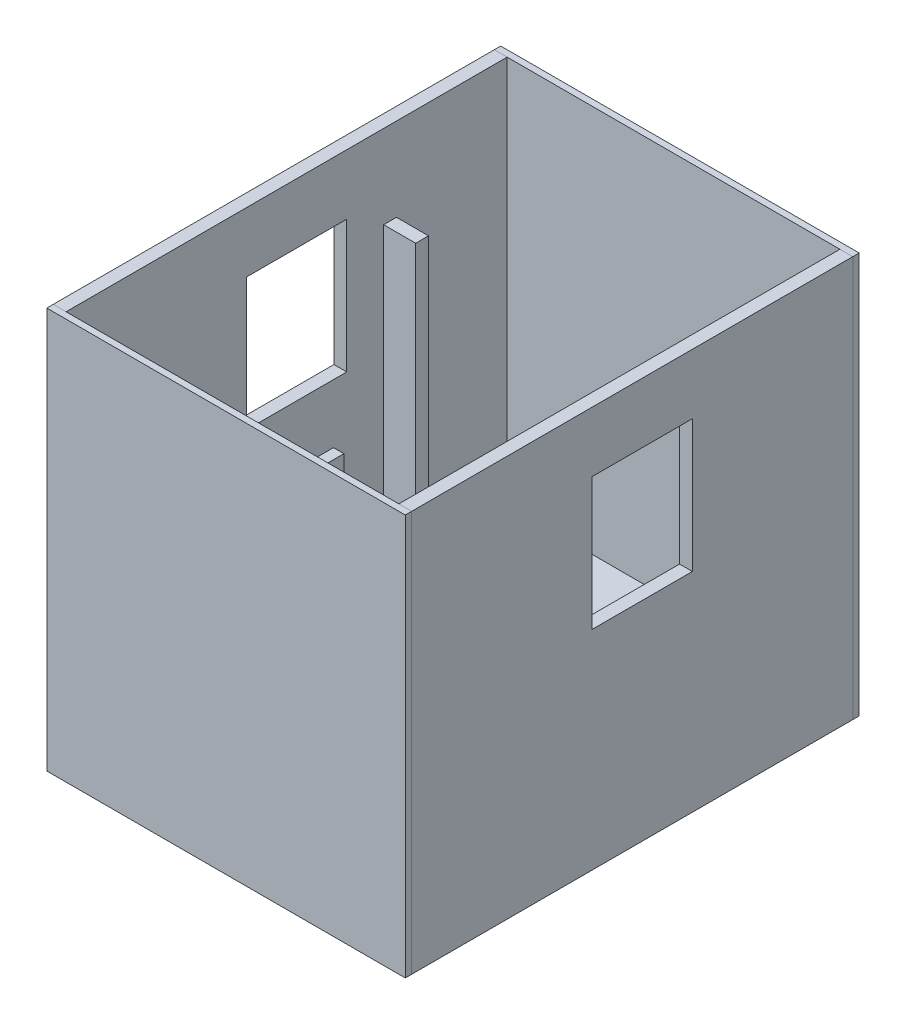
SolidWorks part; units mm, degrees
material "Pin"
ref_plane "Plan de face" through (0, 0, 0) normal (0, 0, 1) x (1, 0, 0)
ref_plane "Plan de dessus" through (0, 0, 0) normal (0, 1, 0) x (1, 0, 0)
ref_plane "Plan de droite" through (0, 0, 0) normal (1, 0, 0) x (0, 0, -1)
sketch "Esquisse1" plane through (0, 0, 0) normal (0, 1, 0) x (1, 0, 0)
  line L1 (0, 0) -> (415, 0)
  line L2 (0, 0) -> (0, 550)
  line L3 (0, 550) -> (415, 550)
  line L4 (415, 0) -> (415, 550)
  dimension "D1" = 550
  dimension "D2" = 415
extrude "Boss.-Extru.1" add sketch "Esquisse1" along normal blind 16
sketch "Esquisse2" plane through (0, 0, -500) normal (1, 0, 0) x (0, 0, -1)
  line L1 (-208, 16) -> (-195, 16)
  line L2 (-208, 16) -> (-208, 43)
  line L3 (-208, 43) -> (-195, 43)
  line L4 (-195, 16) -> (-195, 43)
  line L5 (50, 16) -> (50, 0) construction
  line L6 (-101, 16) -> (-88, 16)
  line L7 (-101, 16) -> (-101, 43)
  line L8 (-101, 43) -> (-88, 43)
  line L9 (-88, 16) -> (-88, 43)
  line L10 (50, 16) -> (-500, 16) construction
  dimension "D1" = 138
  dimension "D2" = 120
  dimension "D3" = 27
  dimension "D4" = 13
extrude "Boss.-Extru.2" add sketch "Esquisse2" along normal blind 335 from offset 40 separate body
sketch "Esquisse3" plane through (0, 0, 0) normal (0, 1, 0) x (1, 0, 0)
  line L0 (0, 0) -> (415, 0) construction
  line L1 (0, 550) -> (-16, 550)
  line L2 (0, 550) -> (0, 0)
  line L3 (0, 0) -> (-16, 0)
  line L4 (-16, 550) -> (-16, 0)
  line L6 (415, 550) -> (431, 550)
  line L7 (415, 550) -> (415, 0)
  line L8 (415, 0) -> (431, 0)
  line L9 (431, 550) -> (431, 0)
  dimension "D1" = 16
extrude "Boss.-Extru.3" add sketch "Esquisse3" along normal blind 500 separate body
sketch "Esquisse4" plane through (-16, 0, 0) normal (-1, 0, 0) x (0, 0, 1)
  line L0 (-550, 500) -> (-550, 0) construction
  line L1 (-350, 425) -> (-225, 425)
  line L2 (-350, 425) -> (-350, 260)
  line L3 (-350, 260) -> (-225, 260)
  line L4 (-225, 425) -> (-225, 260)
  line L5 (-550, 500) -> (0, 500) construction
  line L6 (0, 500) -> (0, 0) construction
  dimension "D1" = 125
  dimension "D2" = 165
  dimension "D3" = 75
  dimension "D4" = 200
  dimension "D5" = 225
extrude "Enlèv. mat.-Extru.1" cut sketch "Esquisse4" against normal through all
sketch "Esquisse5" plane through (0, 16, 0) normal (0, 1, 0) x (1, 0, 0)
  line L0 (0, 550) -> (0, 0) construction
  line L1 (415, 0) -> (415, 550) construction
  line L2 (375, 292) -> (40, 292) construction
  line L8 (0, 141) -> (415, 141)
  line L9 (0, 141) -> (0, 157)
  line L10 (0, 157) -> (415, 157)
  line L11 (415, 141) -> (415, 157)
  dimension "D1" = 16
  dimension "D2" = 135
extrude "Boss.-Extru.4" add sketch "Esquisse5" along normal blind 320 separate body
sketch "Esquisse6" plane through (0, 0, -550) normal (0, 0, -1) x (-1, 0, 0)
  line L1 (-431, 0) -> (16, 0)
  line L2 (-431, 0) -> (-431, 500)
  line L3 (-431, 500) -> (16, 500)
  line L4 (16, 0) -> (16, 500)
extrude "Boss.-Extru.5" add sketch "Esquisse6" along normal blind 8 separate body
sketch "Esquisse7" plane through (0, 0, 0) normal (0, 0, 1) x (1, 0, 0)
  line L1 (-16, 500) -> (431, 500)
  line L2 (-16, 500) -> (-16, 0)
  line L3 (-16, 0) -> (431, 0)
  line L4 (431, 500) -> (431, 0)
extrude "Boss.-Extru.6" add sketch "Esquisse7" along normal blind 8 separate body
sketch "Esquisse8" plane through (0, 500, 0) normal (0, 1, 0) x (1, 0, 0)
  line L1 (-16, 558) -> (431, 558)
  line L2 (-16, 558) -> (-16, -8)
  line L3 (-16, -8) -> (431, -8)
  line L4 (431, 558) -> (431, -8)
extrude "Boss.-Extru.7" [suppressed] add sketch "Esquisse8" along normal blind 8 separate body
sketch "Esquisse9" plane through (0, 16, 0) normal (0, 1, 0) x (1, 0, 0)
  line L0 (0, 0) -> (0, 550) construction
  line L1 (0, 396) -> (40, 396)
  line L2 (0, 396) -> (0, 412)
  line L3 (0, 412) -> (40, 412)
  line L4 (40, 396) -> (40, 412)
  line L8 (415, 0) -> (415, 550) construction
  line L9 (415, 412) -> (375, 412)
  line L10 (415, 412) -> (415, 396)
  line L11 (415, 396) -> (375, 396)
  line L12 (375, 412) -> (375, 396)
  line L13 (375, 412) -> (40, 412) construction
  dimension "D1" = 40
  dimension "D2" = 16
extrude "Boss.-Extru.8" add sketch "Esquisse9" along normal blind 380 separate body
sketch "Esquisse10" plane through (0, 16, 0) normal (0, 1, 0) x (1, 0, 0)
  line L0 (0, 141) -> (415, 141) construction
  line L1 (105, 141) -> (121, 141)
  line L2 (105, 141) -> (105, 0)
  line L3 (105, 0) -> (121, 0)
  line L4 (121, 141) -> (121, 0)
  line L5 (431, 0) -> (-16, 0) construction
  line L6 (0, 0) -> (0, 550) construction
  dimension "D1" = 16
  dimension "D2" = 105
extrude "Boss.-Extru.9" add sketch "Esquisse10" along normal blind 180 separate body
sketch "Esquisse11" plane through (0, 16, 0) normal (0, 1, 0) x (1, 0, 0)
  line L0 (415, 157) -> (0, 157) construction
  line L1 (149.5, 157) -> (162.5, 157)
  line L2 (149.5, 157) -> (149.5, 184)
  line L3 (149.5, 184) -> (162.5, 184)
  line L4 (162.5, 157) -> (162.5, 184)
  line L5 (207.5, 184) -> (207.5, 157) construction
  line L6 (252.5, 157) -> (252.5, 184)
  line L7 (265.5, 184) -> (252.5, 184)
  line L8 (265.5, 157) -> (265.5, 184)
  line L9 (265.5, 157) -> (252.5, 157)
  point P8 (0, 0)
  dimension "D1" = 27
  dimension "D2" = 13
  dimension "D3" = 90
extrude "Boss.-Extru.10" add sketch "Esquisse11" along normal up to surface (320 mm away) separate body up to face at (207.5, 336, -149)
